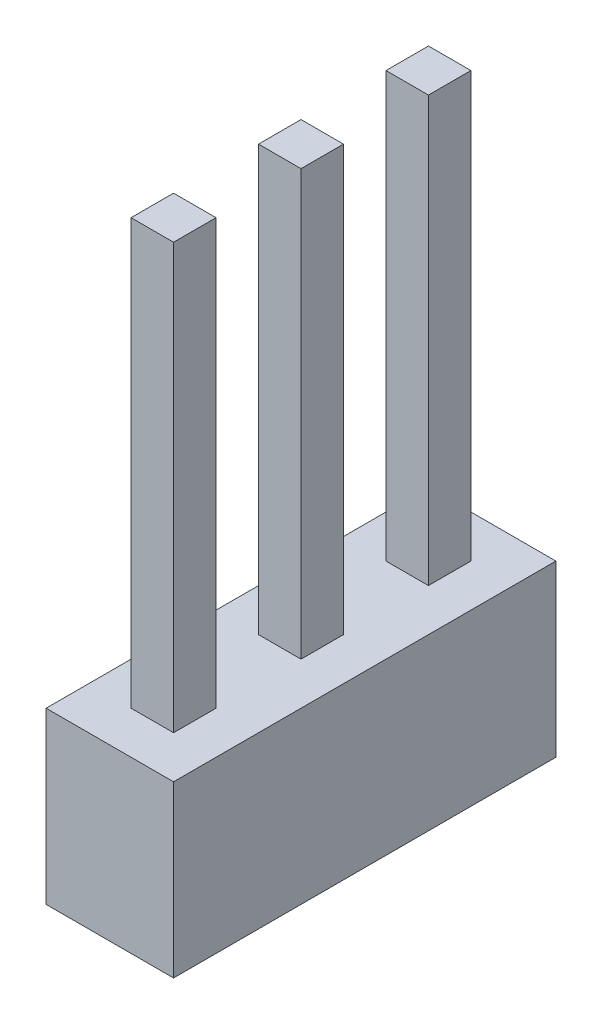
SolidWorks part; units mm, degrees
ref_plane "Front Plane" through (0, 0, 0) normal (0, 0, 1) x (1, 0, 0)
ref_plane "Top Plane" through (0, 0, 0) normal (0, 1, 0) x (1, 0, 0)
ref_plane "Right Plane" through (0, 0, 0) normal (1, 0, 0) x (0, 0, -1)
sketch "Sketch1" plane through (0, 0, 0) normal (0, 1, 0) x (1, 0, 0)
  line L1 (0, 0) -> (2.286, 0)
  line L2 (0, 0) -> (0, 6.858)
  line L3 (0, 6.858) -> (2.286, 6.858)
  line L4 (2.286, 0) -> (2.286, 6.858)
  dimension "D1" = 2.286
  dimension "D2" = 6.858
extrude "Extrude1" add sketch "Sketch1" along normal blind 3.048
sketch "Sketch2" plane through (0, 3.048, 0) normal (0, 1, 0) x (1, 0, 0)
  line L0 (0, 6.858) -> (0, 0) construction
  line L1 (0.762, 0.762) -> (1.524, 0.762)
  line L2 (0.762, 0.762) -> (0.762, 1.524)
  line L3 (0.762, 1.524) -> (1.524, 1.524)
  line L4 (1.524, 0.762) -> (1.524, 1.524)
  line L5 (0.762, 5.334) -> (1.524, 5.334)
  line L6 (0.762, 5.334) -> (0.762, 6.096)
  line L7 (0.762, 6.096) -> (1.524, 6.096)
  line L8 (1.524, 5.334) -> (1.524, 6.096)
  line L9 (0, 0) -> (2.286, 0) construction
  line L10 (2.286, 6.858) -> (0, 6.858) construction
  line L12 (0.762, 3.048) -> (1.524, 3.048)
  line L13 (0.762, 3.048) -> (0.762, 3.81)
  line L14 (0.762, 3.81) -> (1.524, 3.81)
  line L15 (1.524, 3.048) -> (1.524, 3.81)
  dimension "D1" = 0.762
  dimension "D2" = 0.762
  dimension "D3" = 0.762
  dimension "D4" = 0.762
  dimension "D5" = 0.762
  dimension "D6" = 0.762
  dimension "D7" = 0.762
  dimension "D8" = 0.762
  dimension "D9" = 0.762
  dimension "D10" = 0.762
  dimension "D11" = 0.762
  dimension "D12" = 1.524
extrude "Extrude2" add sketch "Sketch2" along normal blind 7.62
